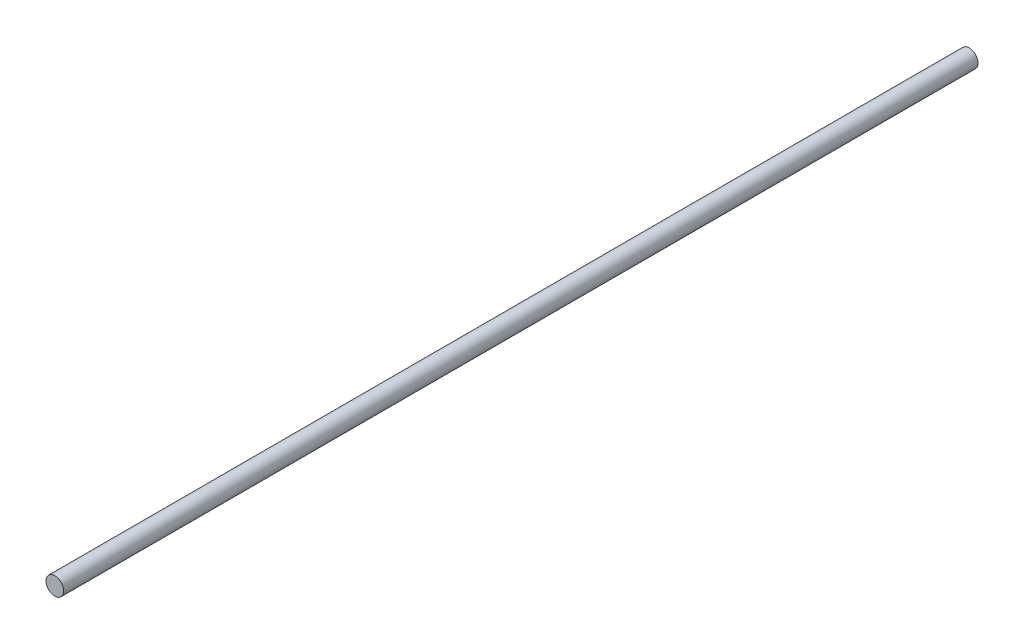
SolidWorks part; units mm, degrees
ref_plane "Front Plane" through (0, 0, 0) normal (0, 0, 1) x (1, 0, 0)
ref_plane "Top Plane" through (0, 0, 0) normal (0, 1, 0) x (1, 0, 0)
ref_plane "Right Plane" through (0, 0, 0) normal (1, 0, 0) x (0, 0, -1)
sketch "Sketch1" plane through (0, 0, 0) normal (0, 0, 1) x (1, 0, 0)
  circle A0 centre (0, 0) radius 1.5
  dimension "D1" = 3
extrude "Boss-Extrude1" add sketch "Sketch1" along normal mid plane 155.35
